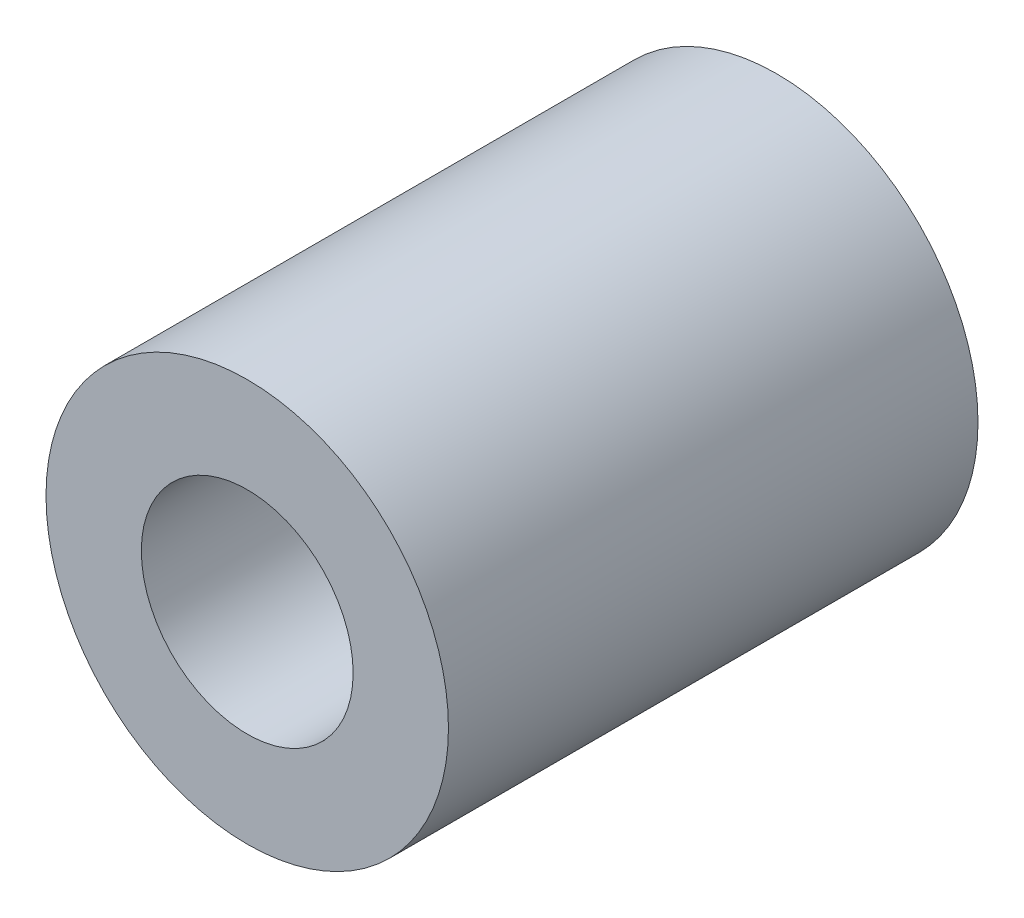
SolidWorks part; units mm, degrees
ref_plane "Plan de face" through (0, 0, 0) normal (0, 0, 1) x (1, 0, 0)
ref_plane "Plan de dessus" through (0, 0, 0) normal (0, 1, 0) x (1, 0, 0)
ref_plane "Plan de droite" through (0, 0, 0) normal (1, 0, 0) x (0, 0, -1)
sketch "Esquisse1" plane through (0, 0, 0) normal (0, 0, 1) x (1, 0, 0)
  circle A0 centre (0, 0) radius 9.5
  circle A1 centre (0, 0) radius 5
  dimension "D1" = 10
  dimension "D2" = 19
extrude "Boss.-Extru.1" add sketch "Esquisse1" along normal blind 25
